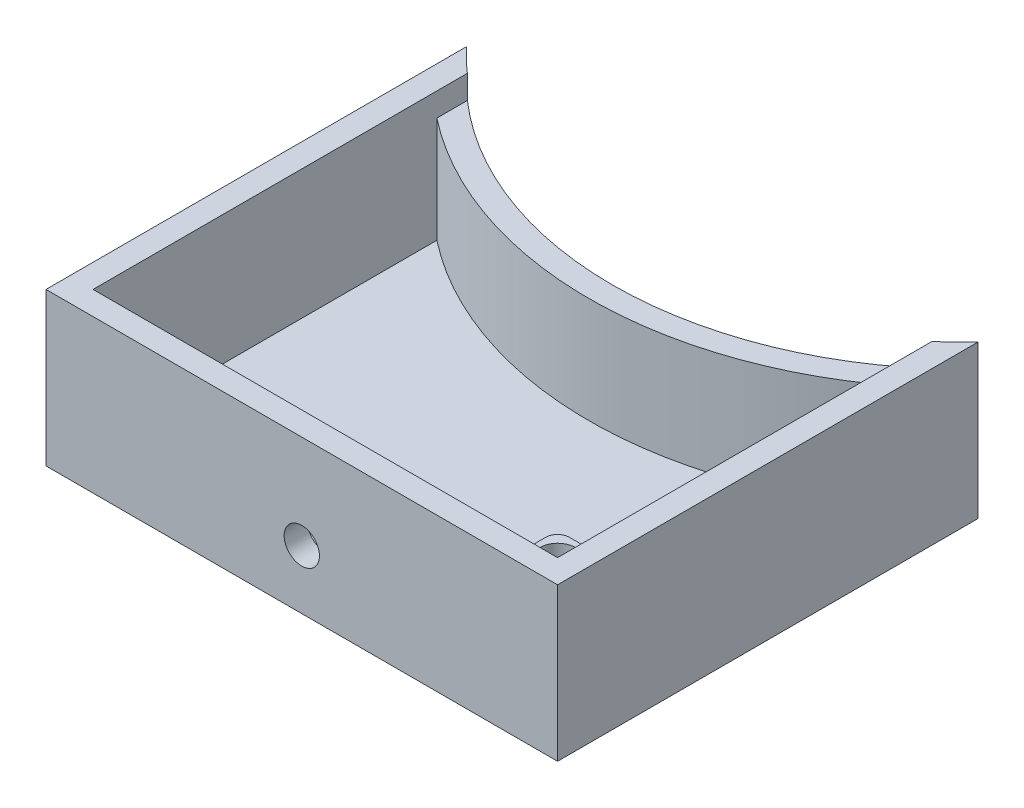
SolidWorks part; units mm, degrees
ref_plane "Front Plane" through (0, 0, 0) normal (0, 0, 1) x (1, 0, 0)
ref_plane "Top Plane" through (0, 0, 0) normal (0, 1, 0) x (1, 0, 0)
ref_plane "Right Plane" through (0, 0, 0) normal (1, 0, 0) x (0, 0, -1)
sketch "Sketch1" plane through (0, 0, 0) normal (0, 1, 0) x (1, 0, 0)
  line L1 (-21.75, 17.875) -> (21.75, 17.875)
  line L2 (-21.75, 17.875) -> (-21.75, -17.875)
  line L3 (-21.75, -17.875) -> (21.75, -17.875)
  line L4 (21.75, 17.875) -> (21.75, -17.875)
  line L5 (-21.75, 17.875) -> (21.75, -17.875) construction
  line L6 (-21.75, -17.875) -> (21.75, 17.875) construction
  circle A0 centre (0, 38.5375) radius 30
  point P0 (0, 0)
  point P8 (0, 0)
  dimension "D3" = 60
  dimension "D1" = 43.5
  dimension "D2" = 35.75
extrude "Boss-Extrude1" add sketch "Sketch1" along normal blind 13 contours A0 L2 L3 L4
shell "Shell1" thickness 2
sketch "Sketch2" plane through (0, 13, 0) normal (0, 1, 0) x (1, 0, 0)
  line L0 (-19.75, 15.9557) -> (-19.75, 13.3594)
  line L1 (19.75, 15.9557) -> (19.75, 13.3594)
  line L2 (-19.75, 13.3594) -> (-19.75, -15.875) construction
  line L3 (19.75, 13.3594) -> (19.75, -15.875) construction
  circle A0 centre (0, 38.5375) radius 30
  arc A1 (-21.75, 17.875) -> (21.75, 17.875) centre (0, 38.5375) ccw construction
  circle A2 centre (0, 38.5375) radius 32
  arc A3 (-19.75, 13.3594) -> (19.75, 13.3594) centre (0, 38.5375) ccw construction
  point P14 (-19.4461, 15.6935)
  point P15 (-19.4717, 13.1435)
  point P16 (0, 0)
  point P17 (0, 0)
  arc M5 (21.75, 17.875) -> (-21.75, 17.875) centre (0, 38.5375) cw
  arc M10 (-19.75, 13.3594) -> (19.75, 13.3594) centre (0, 38.5375) ccw
extrude "Cut-Extrude1" cut sketch "Sketch2" against normal blind 2 contours L1 L0 M5 M10
sketch "Sketch3" plane through (0, 0, 17.875) normal (0, 0, 1) x (1, 0, 0)
  line L0 (-21.75, 0) -> (21.75, 0) construction
  circle A0 centre (0, 5) radius 1.5
  point P2 (0, 0)
  point P5 (0, 0)
  dimension "D1" = 3
  dimension "D2" = 5
extrude "Cut-Extrude2" cut sketch "Sketch3" against normal up to next
sketch "Sketch4" plane through (0, 2, 0) normal (0, 1, 0) x (1, 0, 0)
  line L1 (15.75, -11.875) -> (19.75, -11.875)
  line L2 (15.75, -11.875) -> (15.75, -15.875)
  line L3 (15.75, -15.875) -> (19.75, -15.875)
  line L4 (19.75, -11.875) -> (19.75, -15.875)
  line L5 (15.75, -11.875) -> (19.75, -15.875) construction
  line L6 (15.75, -15.875) -> (19.75, -11.875) construction
  circle A0 centre (17.75, -13.875) radius 1.5
  point P0 (17.75, -13.875)
  dimension "D3" = 3
  dimension "D1" = 4
  dimension "D2" = 4
extrude "Boss-Extrude2" add sketch "Sketch4" along normal up to surface (9 mm away) up to face at (0, 11, -11.0975)
fillet "Fillet1" radius 1 1 edges at (15.75, 6.5, 11.875)
